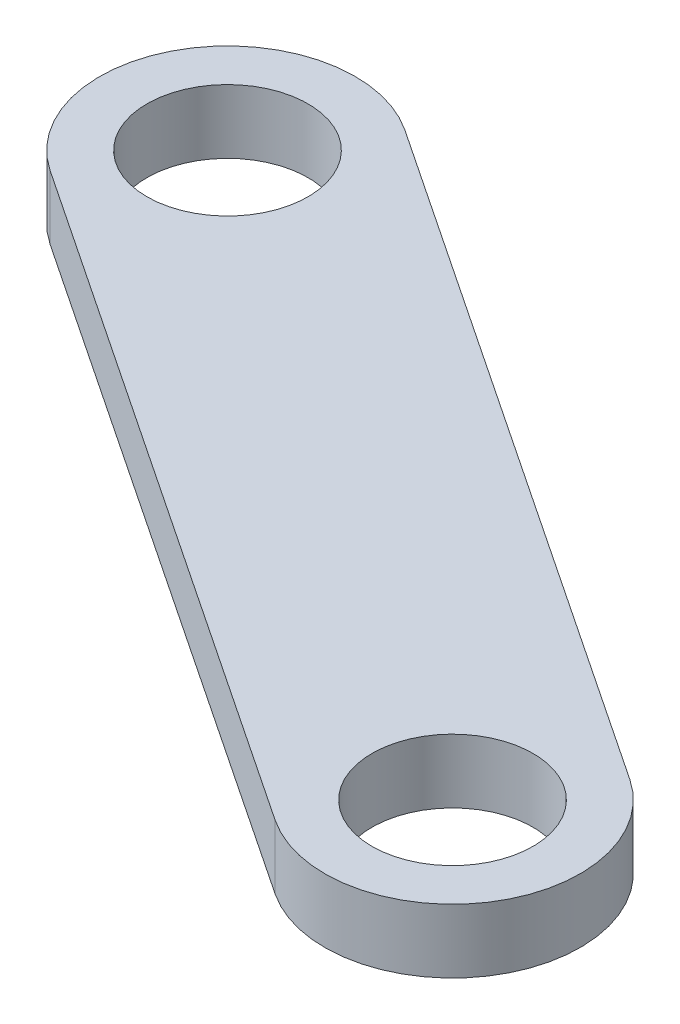
SolidWorks part; units mm, degrees
material "5052-H32"
ref_plane "X-Y Datum" through (0, 0, 0) normal (0, 0, 1) x (1, 0, 0)
ref_plane "X-Z Datum" through (0, 0, 0) normal (0, 1, 0) x (1, 0, 0)
ref_plane "Y-Z Datum" through (0, 0, 0) normal (1, 0, 0) x (0, 0, -1)
sketch "Sketch1" plane through (0, 0, 0) normal (0, 1, 0) x (1, 0, 0)
  line L11 (16.764, -11.176) -> (0, 0) construction
  line L12 (16.764, -11.176) -> (15.0028, -13.8178) construction
  line L13 (15.0028, -13.8178) -> (-1.7612, -2.6418)
  line L14 (18.5252, -8.5342) -> (1.7612, 2.6418)
  line L16 (1.7612, 2.6418) -> (0, 0) construction
  circle A8 centre (0, 0) radius 2
  circle A9 centre (16.764, -11.176) radius 2
  arc A11 (18.5252, -8.5342) -> (15.0028, -13.8178) centre (16.764, -11.176) cw
  arc A14 (-1.7612, -2.6418) -> (1.7612, 2.6418) centre (0, 0) cw
  point P6 (0, 0)
  dimension "D1" = 4
  dimension "D4" = 3.175
  dimension "D2" = 16.764
  dimension "D3" = 11.176
extrude "Boss-Extrude1" add sketch "Sketch1" along normal blind 1.5875
